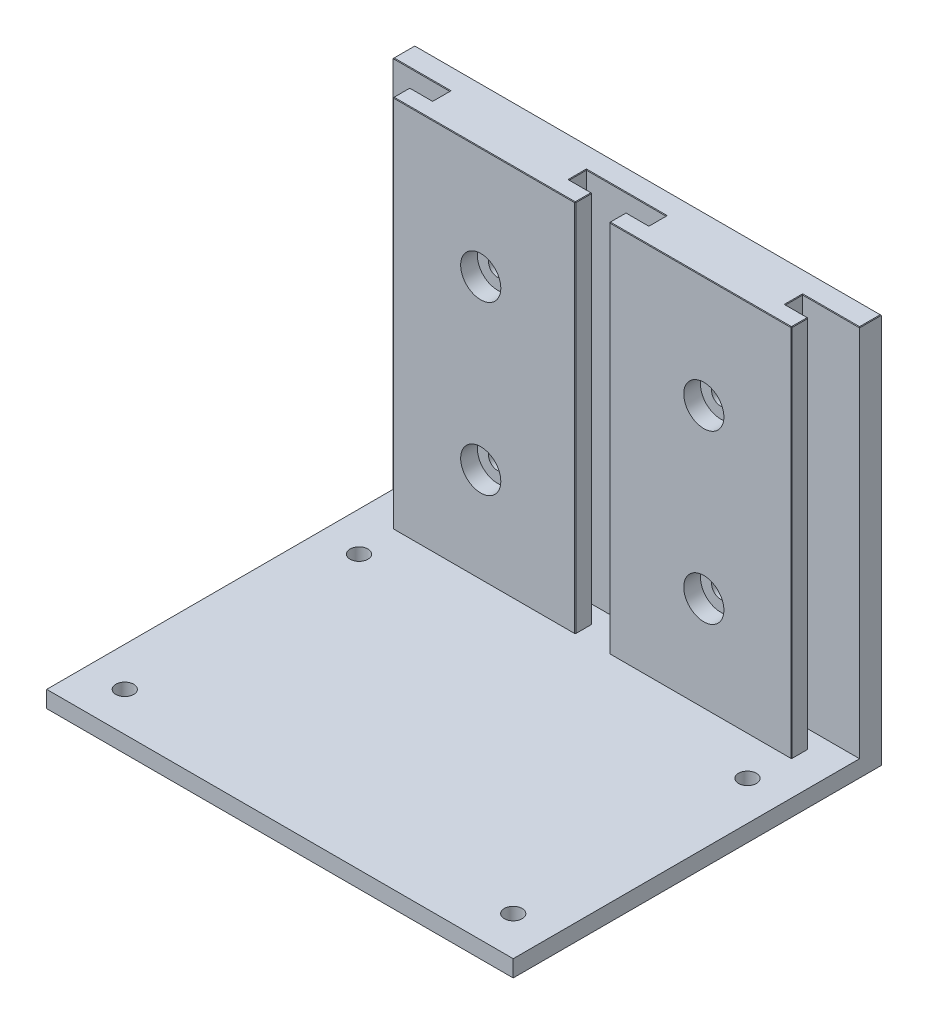
SolidWorks part; units mm, degrees
ref_plane "Front Plane" through (0, 0, 0) normal (0, 0, 1) x (1, 0, 0)
ref_plane "Top Plane" through (0, 0, 0) normal (0, 1, 0) x (1, 0, 0)
ref_plane "Right Plane" through (0, 0, 0) normal (1, 0, 0) x (0, 0, -1)
sketch "Sketch1" plane through (0, 0, 0) normal (0, 1, 0) x (1, 0, 0)
  line L0 (-38.825, 25) -> (38.825, 25) construction
  line L1 (-41.825, -28) -> (41.825, -28)
  line L2 (-41.825, -28) -> (-41.825, 28)
  line L3 (-41.825, 28) -> (41.825, 28)
  line L4 (41.825, -28) -> (41.825, 28)
  line L5 (-41.825, -28) -> (41.825, 28) construction
  line L6 (-41.825, 28) -> (41.825, -28) construction
  line L7 (38.825, -25) -> (38.825, 25) construction
  line L8 (-38.825, -25) -> (38.825, -25) construction
  line L9 (-38.825, -25) -> (-38.825, 25) construction
  circle A0 centre (-34.825, -21) radius 1.6
  circle A1 centre (34.825, -21) radius 1.6
  circle A2 centre (34.825, 21) radius 1.6
  circle A3 centre (-34.825, 21) radius 1.6
  point P0 (0, 0)
  dimension "D7" = 3.2
  dimension "D1" = 83.65
  dimension "D2" = 56
  dimension "D4" = 4
  dimension "D5" = 4
  dimension "D6" = 4
  dimension "D8" = 4
  dimension "D3" = 3
extrude "Boss-Extrude1" add sketch "Sketch1" along normal blind 3
sketch "Sketch2" plane through (0, 0, 0) normal (0, 1, 0) x (1, 0, 0)
  line L0 (0, 0) -> (0, 50000) construction
  line L2 (41.825, 38) -> (-41.825, 38)
  line L3 (41.825, 38) -> (41.825, 28)
  line L4 (41.825, 28) -> (-41.825, 28)
  line L5 (-41.825, 38) -> (-41.825, 28)
  line L6 (41.825, 38) -> (-41.825, 28) construction
  line L7 (41.825, 28) -> (-41.825, 38) construction
  line L8 (41.825, 28) -> (-41.825, 28) construction
  point P3 (0, 33)
  dimension "D1" = 10
extrude "Boss-Extrude2" add sketch "Sketch2" along normal blind 70
sketch "Sketch3" plane through (0, 70, 0) normal (0, 1, 0) x (1, 0, 0)
  line L0 (0, 0) -> (0, 50000) construction
  line L1 (-35.725, 34.1) -> (-41.825, 34.1)
  line L2 (-35.725, 34.1) -> (-35.725, 28)
  line L3 (-35.725, 28) -> (-41.825, 28)
  line L4 (-41.825, 34.1) -> (-41.825, 28)
  line L5 (-35.725, 34.1) -> (-41.825, 28) construction
  line L6 (-35.725, 28) -> (-41.825, 34.1) construction
  line L7 (-31.625, 31) -> (-35.725, 31)
  line L8 (-31.625, 31) -> (-31.625, 34.1)
  line L9 (-31.625, 34.1) -> (-35.725, 34.1)
  line L11 (-31.625, 31) -> (-35.725, 34.1) construction
  line L12 (-31.625, 34.1) -> (-35.725, 31) construction
  line L13 (31.625, 34.1) -> (35.725, 31) construction
  line L14 (31.625, 31) -> (35.725, 34.1) construction
  line L15 (35.725, 28) -> (41.825, 34.1) construction
  line L16 (35.725, 34.1) -> (41.825, 28) construction
  line L18 (31.625, 34.1) -> (35.725, 34.1)
  line L19 (31.625, 31) -> (31.625, 34.1)
  line L20 (31.625, 31) -> (35.725, 31)
  line L21 (41.825, 34.1) -> (41.825, 28)
  line L22 (35.725, 28) -> (41.825, 28)
  line L23 (35.725, 34.1) -> (35.725, 28)
  line L24 (35.725, 34.1) -> (41.825, 34.1)
  line L25 (-41.825, 28) -> (41.825, 28) construction
  line L26 (3.05, 34.1) -> (-3.05, 34.1)
  line L27 (3.05, 34.1) -> (3.05, 28)
  line L28 (3.05, 28) -> (-3.05, 28)
  line L29 (-3.05, 34.1) -> (-3.05, 28)
  line L30 (3.05, 34.1) -> (-3.05, 28) construction
  line L31 (3.05, 28) -> (-3.05, 34.1) construction
  line L32 (3.05, 34.1) -> (7.15, 31) construction
  line L33 (-3.05, 31) -> (-7.15, 31)
  line L35 (-3.05, 34.1) -> (-7.15, 34.1)
  line L36 (-7.15, 31) -> (-7.15, 34.1)
  line L37 (-3.05, 31) -> (-7.15, 34.1) construction
  line L38 (-3.05, 34.1) -> (-7.15, 31) construction
  line L39 (3.05, 31) -> (7.15, 34.1) construction
  line L40 (7.15, 31) -> (7.15, 34.1)
  line L41 (3.05, 34.1) -> (7.15, 34.1)
  line L43 (3.05, 31) -> (7.15, 31)
  point P0 (-38.775, 31.05)
  point P6 (-33.675, 32.55)
  point P20 (33.675, 32.55)
  point P21 (38.775, 31.05)
  point P22 (0, 31.05)
  point P29 (-5.1, 32.55)
  point P37 (5.1, 32.55)
  line M12 (-41.825, 38) -> (-41.825, 28)
  line M13 (-41.825, 28) -> (41.825, 28)
  line M14 (41.825, 28) -> (41.825, 38)
  dimension "D1" = 6.1
  dimension "D2" = 4.1
  dimension "D3" = 3.1
extrude "Cut-Extrude1" cut sketch "Sketch3" against normal up to surface (67 mm away) contours L26 L29 L27 M13 | L36 L33 L29 L35 | L27 L43 L40 L41 | L23 L18 L19 L20 | L24 L23 M13 M14 | L8 L9 L2 L7 | L2 L1 M12 M13 up to face at (0, 3, 0)
chamfer "Chamfer1" distance 0.1 angle 45 8 edges at (-35.725, 36.5, -28) (-35.725, 36.5, -31) (3.05, 36.5, -31) (3.05, 36.5, -28) (35.725, 36.5, -31) (35.725, 36.5, -28) (-3.05, 36.5, -31) (-3.05, 36.5, -28)
chamfer "Chamfer2" distance 0.1 angle 45 28 edges at (-35.675, 70, -30.95) (-33.625, 70, -31) (-31.625, 70, -32.55) (-36.725, 70, -34.1) (-41.825, 70, -36.05) (0, 70, -38) (41.825, 70, -36.05) (36.725, 70, -34.1) (31.625, 70, -32.55) (33.625, 70, -31) (35.675, 70, -30.95) (35.725, 70, -29.5) (35.675, 70, -28.05) (19.3875, 70, -28) (3.1, 70, -28.05) (3.05, 70, -29.5) (3.1, 70, -30.95) (5.15, 70, -31) (7.15, 70, -32.55) (0, 70, -34.1) (-7.15, 70, -32.55) (-5.15, 70, -31) (-3.1, 70, -30.95) (-3.05, 70, -29.5) (-3.1, 70, -28.05) (-19.3875, 70, -28) (-35.675, 70, -28.05) (-35.725, 70, -29.5)
sketch "Sketch4" plane through (0, 0, -38) normal (0, 0, -1) x (-1, 0, 0)
  line L0 (-1000, 0) -> (49000, 0) construction
  line L1 (0, 0) -> (0, 72.9506) construction
  circle A0 centre (-20, 20) radius 1.6
  circle A1 centre (-20, 50) radius 1.6
  circle A2 centre (20, 20) radius 1.6
  circle A3 centre (20, 50) radius 1.6
  dimension "D1" = 3.2
  dimension "D3" = 20
  dimension "D2" = 30
  dimension "D4" = 20
extrude "Cut-Extrude2" cut sketch "Sketch4" against normal up to surface (10 mm away) up to face at (19.3875, 36.45, -28)
sketch "Sketch5" plane through (0, 0, -28) normal (0, 0, 1) x (1, 0, 0)
  line L0 (-1000, 0) -> (49000, 0) construction
  line L1 (0, 0) -> (0, 83.3807) construction
  circle A5 centre (-20, 50) radius 3.6
  circle A6 centre (-20, 50) radius 3.6
  circle A7 centre (20, 20) radius 3.6
  circle A8 centre (-20, 20) radius 3.6
  circle A9 centre (-20, 20) radius 3.6
  circle A10 centre (20, 50) radius 3.6
  circle M4 centre (-20, 20) radius 1.6
  dimension "D1" = 2
  dimension "D2" = 2
extrude "Cut-Extrude3" cut sketch "Sketch5" against normal blind 3 contours A9 M4 | A7 | A10 | A6
